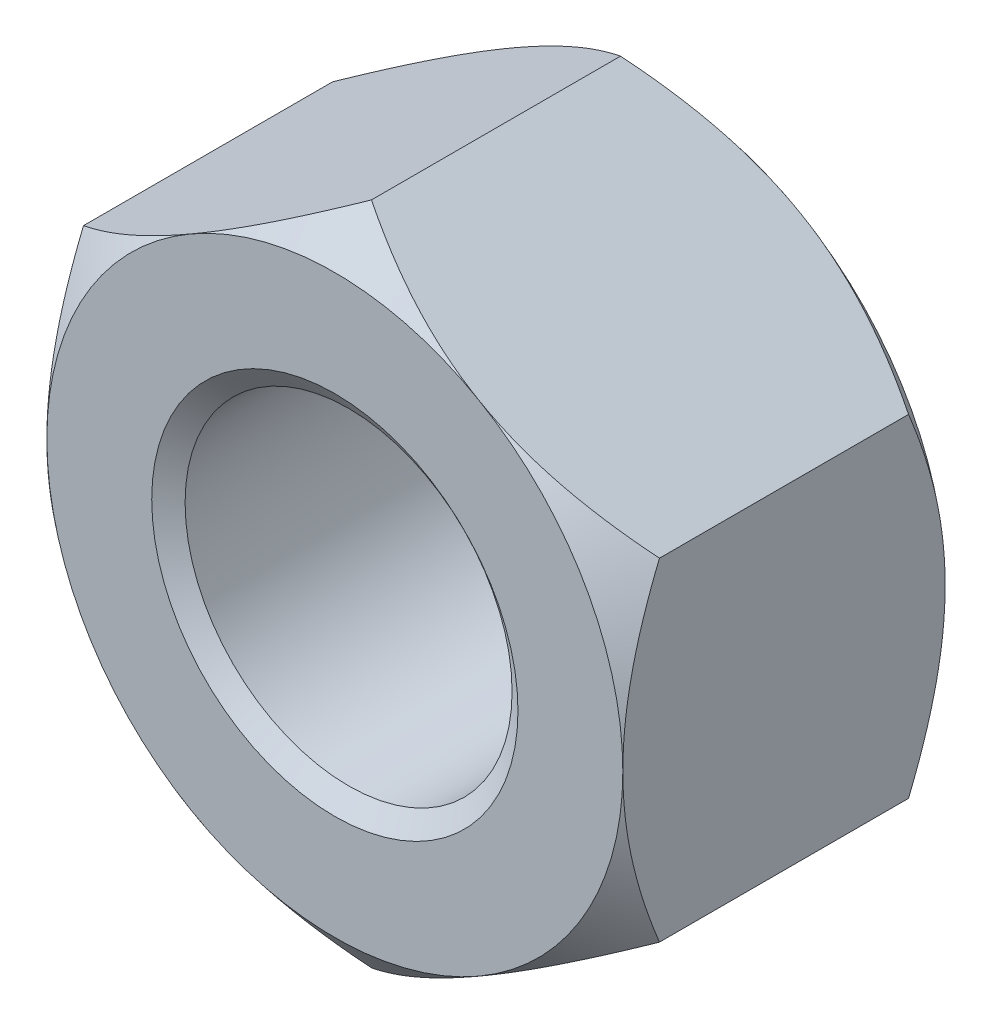
SolidWorks part; units mm, degrees
extrude "BaseNut" add sketch "BaseNutSke" against normal blind 9.779
sketch "BaseNutSke" plane through (0, 0, 0) normal (0, 0, 1) x (1, 0, 0)
  line L6 (8.7376, 5.0447) -> (8.7376, -5.0447)
  line L7 (-8.7376, 5.0447) -> (-8.7376, -5.0447)
  line L8 (8.7376, 5.0447) -> (0, 10.0893)
  line L9 (0, 10.0893) -> (-8.7376, 5.0447)
  line L10 (-8.7376, -5.0447) -> (0, -10.0893)
  line L11 (0, -10.0893) -> (8.7376, -5.0447)
  circle A0 centre (0, 0) radius 4.9606
  dimension "Tap_drill" = 9.9212
  dimension "Width_flats" = 17.4752
  dimension "D2" = 8.7376
  dimension "D3" = 8.7376
  dimension "D1" = 120
  dimension "D4" = 8.7376
cosmetic thread "ThreadCosmetic" [suppressed] parameters "Thread_major"=11.1125
pattern_linear "ThdSchPat" [suppressed]
revolve "ThreadSchematic" [suppressed] cut sketch "ThdSchSke" angle 360 about L6
sketch "ThdSchSke" plane through (0, 0, 0) normal (0, 1, 0) x (1, 0, 0)
  line L0 (-5.5562, 0.0254) -> (-4.9606, 0.4425)
  line L1 (-4.9606, 0.4425) -> (-2.4803, 0.4425)
  line L2 (-2.4803, 0.4425) -> (-2.4803, -0.3917)
  line L3 (-2.4803, -0.3917) -> (-4.9606, -0.3917)
  line L4 (-4.9606, -0.3917) -> (-5.5562, 0.0254)
  line L5 (-3.175, 1.27) -> (3.175, 1.27) construction
  line L6 (0, 1.27) -> (0, -2.9874) construction
  line L7 (0, 9.3365) -> (0, 0.4171) construction
  dimension "Thread_major" = 11.1125
  dimension "SideAngle" = 55
  dimension "Advance" = 1.27
  dimension "D1" = 0.0254
ref_plane "Plane1" through (0, 0, 0) normal (0, 0, 1) x (1, 0, 0)
ref_plane "Plane2" through (0, 0, 0) normal (0, 1, 0) x (1, 0, 0)
ref_plane "Plane3" through (0, 0, 0) normal (1, 0, 0) x (0, 0, -1)
sketch "Sketch4" plane through (0, 0, 0) normal (1, 0, 0) x (0, 0, -1)
  line L0 (9.779, 8.7376) -> (9.3726, 8.7376)
  line L1 (9.779, 8.7376) -> (9.779, 22.7893)
  line L2 (9.3726, 22.7893) -> (9.779, 22.7893)
  line L3 (9.3726, 22.7893) -> (9.3726, 8.7376)
  line L4 (0, 0) -> (34.925, 0) construction
  line L6 (9.779, 5.0447) -> (9.779, 10.0893) construction
  line L7 (0, 8.7376) -> (-12.7, 8.7376)
  line L8 (0, 5.0447) -> (0, 10.0893) construction
  line L9 (1.1112, 10.0893) -> (1.1113, 22.7893)
  line L10 (1.1113, 22.7893) -> (-12.7, 22.7893)
  line L11 (-12.7, 22.7893) -> (-12.7, 8.7376)
  line L12 (0, 8.7376) -> (1.1112, 10.0893)
  line L14 (0, 5.0447) -> (0, -5.0447) construction
  line L15 (9.779, 10.0893) -> (0, 10.0893) construction
  dimension "D1" = 8.7376
  dimension "D2" = 1.1113
  dimension "D3" = 12.7
  dimension "D4" = 12.7
revolve "Bearing-Face" [suppressed] cut sketch "Sketch4" angle 360 about L4
sketch "Sketch3" plane through (0, 0, 0) normal (1, 0, 0) x (0, 0, -1)
  line L0 (9.779, 8.7376) -> (8.6677, 10.0893)
  line L1 (8.6677, 10.0893) -> (8.6677, 22.7893)
  line L2 (8.6677, 22.7893) -> (22.479, 22.7893)
  line L3 (22.479, 22.7893) -> (22.479, 8.7376)
  line L4 (22.479, 8.7376) -> (9.779, 8.7376)
  line L5 (9.779, 5.0447) -> (9.779, 10.0893) construction
  line L6 (9.779, 10.0893) -> (0, 10.0893) construction
  line L7 (0, 0) -> (38.6776, 0) construction
  line L8 (9.779, 0) -> (0, 0) construction
  line L9 (4.8895, 10.0893) -> (4.8895, 44.222) construction
  line L10 (1.1113, 22.7893) -> (-12.7, 22.7893)
  line L11 (-12.7, 22.7893) -> (-12.7, 8.7376)
  line L12 (-12.7, 8.7376) -> (0, 8.7376)
  line L13 (0, 8.7376) -> (1.1113, 10.0893)
  line L14 (1.1113, 10.0893) -> (1.1113, 22.7893)
  line L16 (9.779, 10.0893) -> (0, 10.0893) construction
  dimension "D1" = 8.7376
  dimension "D2" = 1.1113
  dimension "D4" = 12.7
  dimension "D3" = 12.7
revolve "Double-Chamfer" cut sketch "Sketch3" angle 360 about L7
sketch "Sketch5" plane through (0, 0, 0) normal (1, 0, 0) x (0, 0, -1)
  line L0 (9.7536, 5.5563) -> (9.2948, 4.9011)
  line L1 (9.8044, 5.5563) -> (9.7536, 5.5563)
  line L2 (9.8044, 5.5563) -> (9.8044, 4.9011)
  line L3 (9.8044, 4.9011) -> (9.2948, 4.9011)
  line L6 (-0.0508, 5.5563) -> (0, 5.5563)
  line L7 (0, 5.5563) -> (0.4588, 4.9011)
  line L9 (0.4588, 4.9011) -> (-0.0508, 4.9011)
  line L10 (-0.0508, 4.9011) -> (-0.0508, 5.5563)
  line L11 (25.0375, 0) -> (38.388, 0) construction
  line L12 (9.779, 0) -> (0, 0) construction
  dimension "D1" = 35
  dimension "D2" = 0.0508
  dimension "ThreadMajor" = 5.5562
  dimension "Offset1" = 9.8044
revolve "EndChamfer" cut sketch "Sketch5" angle 360 about L11
equation "\"D2@BaseNutSke\" = \"Width_flats@BaseNutSke\" / 2"
equation "\"D3@BaseNutSke\" = \"Width_flats@BaseNutSke\" / 2"
equation "\"D1@Sketch3\" = \"Width_flats@BaseNutSke\" /2"
equation "\"D2@Sketch3\" = \"Thread_major@ThreadCosmetic\" *.1"
equation "\"D1@Sketch4\" = \"D2@BaseNutSke\""
equation "\"D2@Sketch4\" = \"Thread_major@ThreadCosmetic\" *.10"
equation "\"D4@BaseNutSke\" = \"D3@BaseNutSke\""
equation "\"Thread_major@ThdSchSke\" = \"Thread_major@ThreadCosmetic\""
equation "\"Tap_Drill@ThdSchSke\" = \"Tap_drill@BaseNutSke\""
equation "\"OverCut@ThdSchSke\" = \"Tap_Drill@ThdSchSke\" * 0.5"
equation "\"Num_threads@ThdSchPat\" = int(  ( \"Thickness@BaseNut\" - 0.002 ) / \"Advance@ThdSchSke\" + 0.999 )  + 1"
equation "\"Advance@ThdSchPat\" = ( \"Thickness@BaseNut\" - 0.002 ) /  (\"Num_threads@ThdSchPat\" - 1) 'relax it"
equation "' \"Num_threads@ThdSchPat\" = \"Num_threads@ThdSchPat\" - sgn( \"Num_threads@ThdSchPat\" - 1) '---chamfered tips only---"
equation "\"ThreadMajor@Sketch5\" = \"Thread_major@ThreadCosmetic\" * 0.5"
equation "\"ChamferDepth@Sketch5\" = (\"Thread_major@ThreadCosmetic\" - \"Tap_drill@BaseNutSke\") * 0.55"
equation "\"Offset1@Sketch5\" = \"Thickness@BaseNut\" + 0.001"
equation "\"Offset2@Sketch5\" = \"Offset1@Sketch5\" + 0.002"
